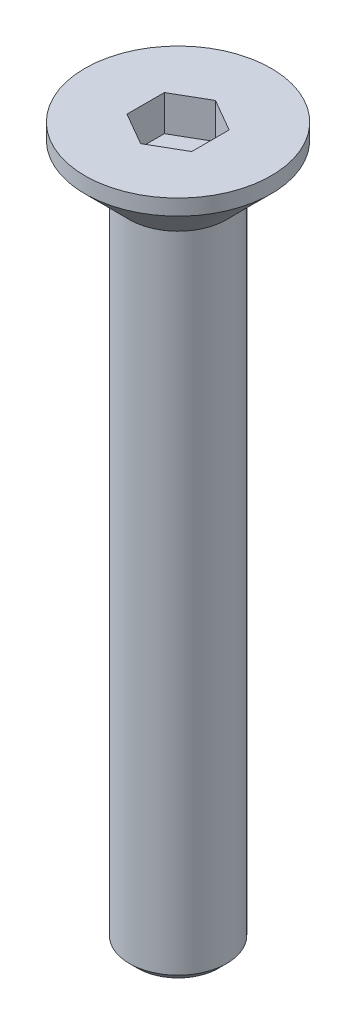
SolidWorks part; units mm, degrees
material "ASTM A36 Steel"
ref_plane "Front Plane" through (0, 0, 0) normal (0, 0, 1) x (1, 0, 0)
ref_plane "Top Plane" through (0, 0, 0) normal (0, 1, 0) x (1, 0, 0)
ref_plane "Right Plane" through (0, 0, 0) normal (1, 0, 0) x (0, 0, -1)
sketch "Sketch1" plane through (0, 0, 0) normal (0, 0, 1) x (1, 0, 0)
  line L0 (0, 0) -> (0, -22)
  line L1 (0, 0) -> (-2.875, 0)
  line L2 (-2.875, -0.485) -> (-1.5, -1.86)
  line L3 (-1.5, -1.86) -> (-1.5, -21.75)
  line L4 (-1.25, -22) -> (0, -22)
  line L5 (-2.875, 0) -> (-2.875, -0.485)
  line L6 (-1.5, -21.75) -> (-1.25, -22)
  point P6 (-1.5, -22)
  dimension "D1" = 1.86
  dimension "D2" = 2.875
  dimension "D3" = 1.5
  dimension "D4" = 45
  dimension "D5" = 22
revolve "Revolve1" add sketch "Sketch1" angle 360 about L0
sketch "Sketch2" plane through (0, 0, 0) normal (0, 1, 0) x (1, 0, 0)
  line L1 (-1, 0.5774) -> (-1, -0.5774)
  line L2 (-1, -0.5774) -> (0, -1.1547)
  line L3 (0, -1.1547) -> (1, -0.5774)
  line L4 (1, -0.5774) -> (1, 0.5774)
  line L5 (1, 0.5774) -> (0, 1.1547)
  line L6 (0, 1.1547) -> (-1, 0.5774)
  circle A0 centre (0, 0) radius 1 construction
  dimension "D1" = 2
extrude "Cut-Extrude1" cut sketch "Sketch2" against normal blind 1.1
